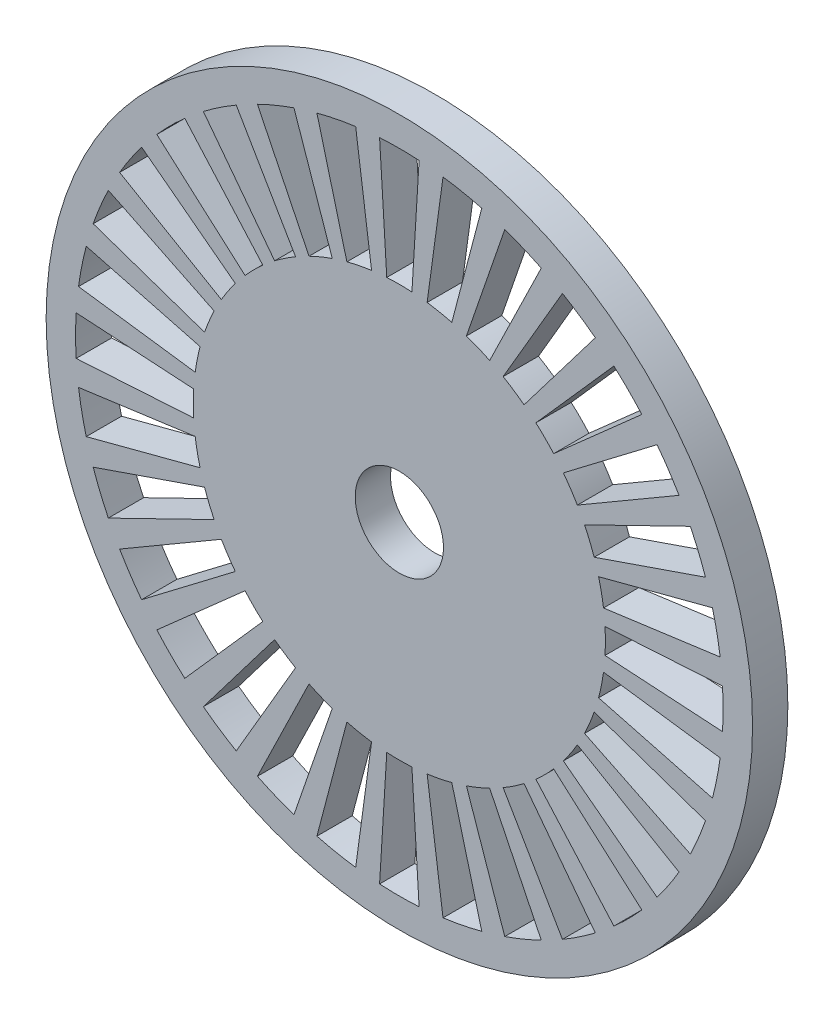
SolidWorks part; units mm, degrees
ref_plane "Front Plane" through (0, 0, 0) normal (0, 0, 1) x (1, 0, 0)
ref_plane "Top Plane" through (0, 0, 0) normal (0, 1, 0) x (1, 0, 0)
ref_plane "Right Plane" through (0, 0, 0) normal (1, 0, 0) x (0, 0, -1)
sketch "Sketch2" plane through (0, 0, 0) normal (0, 0, 1) x (1, 0, 0)
  circle A0 centre (0, 0) radius 12
  circle A1 centre (0, 0) radius 1.5
  dimension "D1" = 3
  dimension "D2" = 24
extrude "Boss-Extrude1" add sketch "Sketch2" along normal blind 1.2
sketch "Sketch3" plane through (0, 0, 1.2) normal (0, 0, 1) x (1, 0, 0)
  line L0 (0, 0) -> (0, 12) construction
  line L1 (0, 0) -> (0.6715, 10.9795)
  line L2 (0, 0) -> (-0.6715, 10.9795)
  circle A0 centre (0, 0) radius 7
  circle A2 centre (0, 0) radius 11
  point P3 (2.325, 10.7535)
  point P8 (-2.325, 10.7535)
  dimension "D1" = 14
  dimension "D2" = 22
  dimension "D3" = 3.5
  dimension "D4" = 3.5
extrude "Cut-Extrude1" cut sketch "Sketch3" against normal blind 1.2 contours A0 L0 A2 L2 | L0 A0 L1 A2
pattern_circular "CirPattern1" count 32 over 360 about axis through (0, 0, 0) along (0, 0, 1) of "Cut-Extrude1"
